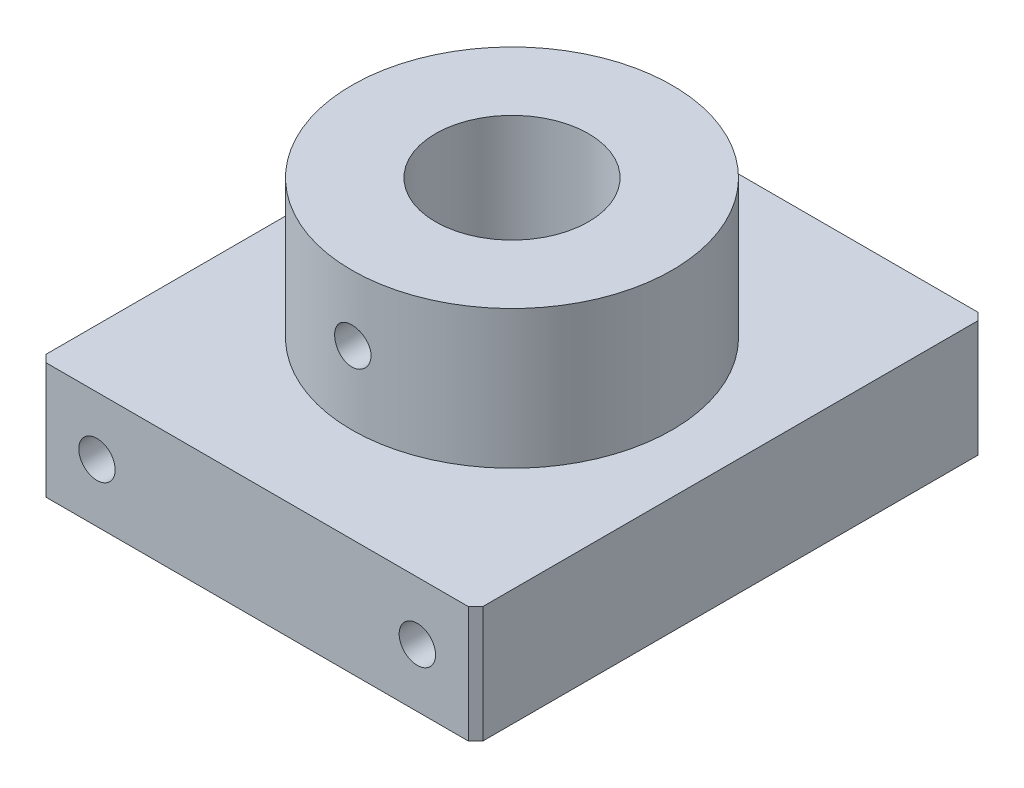
SolidWorks part; units mm, degrees
material "6061 合金"
ref_plane "前视基准面" through (0, 0, 0) normal (0, 0, 1) x (1, 0, 0)
ref_plane "上视基准面" through (0, 0, 0) normal (0, 1, 0) x (1, 0, 0)
ref_plane "右视基准面" through (0, 0, 0) normal (1, 0, 0) x (0, 0, -1)
sketch "草图1" plane through (0, 0, 0) normal (0, 1, 0) x (1, 0, 0)
  line L1 (-15, 17.5) -> (15, 17.5)
  line L2 (-15, 17.5) -> (-15, -17.5)
  line L3 (-15, -17.5) -> (15, -17.5)
  line L4 (15, 17.5) -> (15, -17.5)
  line L5 (-15, 17.5) -> (15, -17.5) construction
  line L6 (-15, -17.5) -> (15, 17.5) construction
  point P0 (0, 0)
  dimension "D1" = 35
  dimension "D2" = 30
extrude "凸台-拉伸1" add sketch "草图1" along normal blind 10
sketch "草图2" plane through (0, 0, 17.5) normal (0, 0, 1) x (1, 0, 0)
  line L0 (0, 0) -> (0, 10) construction
  line L4 (-15, 10) -> (15, 10) construction
  circle A0 centre (-11, 5) radius 1.25
  circle A1 centre (11, 5) radius 1.25
  dimension "D1" = 2.5
sketch "草图3" plane through (0, 10, 0) normal (0, 1, 0) x (1, 0, 0)
  circle A0 centre (0, 0) radius 11
  circle A1 centre (0, 0) radius 5.25
  dimension "D1" = 22
  dimension "D2" = 10.5
extrude "凸台-拉伸2" add sketch "草图3" along normal blind 8.5
sketch "草图4" plane through (0, 0, 0) normal (0, 0, 1) x (1, 0, 0)
  line L1 (5.25, 18.5) -> (-5.25, 18.5) construction
  circle A0 centre (0, 14) radius 1.25
  dimension "D1" = 2.5
  dimension "D2" = 4.5
chamfer "倒角1" distance 0.5 angle 45 4 edges at (15, 5, -17.5) (-15, 5, -17.5) (-15, 5, 17.5) (15, 5, 17.5)
sketch "草图6" plane through (0, 18.5, 0) normal (0, 1, 0) x (1, 0, 0)
  circle A0 centre (0, 0) radius 5.25
extrude "切除-拉伸3" cut sketch "草图6" against normal through all
sketch "草图7" plane through (0, 0, 0) normal (0, -1, 0) x (1, 0, 0)
  line L1 (-15.5971, 18.4355) -> (15.5971, 18.4355)
  line L2 (-15.5971, 18.4355) -> (-15.5971, -18.4355)
  line L3 (-15.5971, -18.4355) -> (15.5971, -18.4355)
  line L4 (15.5971, 18.4355) -> (15.5971, -18.4355)
  line L5 (-15.5971, 18.4355) -> (15.5971, -18.4355) construction
  line L6 (-15.5971, -18.4355) -> (15.5971, 18.4355) construction
  point P0 (0, 0)
extrude "切除-拉伸4" cut sketch "草图7" against normal blind 1
sketch "草图8" plane through (0, 10, 0) normal (0, 1, 0) x (1, 0, 0)
  line L1 (-16.7439, 18.8942) -> (16.7439, 18.8942)
  line L2 (-16.7439, 18.8942) -> (-16.7439, -18.8942)
  line L3 (-16.7439, -18.8942) -> (16.7439, -18.8942)
  line L4 (16.7439, 18.8942) -> (16.7439, -18.8942)
  line L5 (-16.7439, 18.8942) -> (16.7439, -18.8942) construction
  line L6 (-16.7439, -18.8942) -> (16.7439, 18.8942) construction
  circle A0 centre (0, 0) radius 11
extrude "切除-拉伸5" cut sketch "草图8" against normal blind 1
hole_wizard "M3 螺纹孔1" positions "3D草图1" profile "草图9" tap size "M3" standard "GB"
sketch3d "3D草图1"
  point P0 (-11, 5, 17.5)
  point P3 (11, 5, 17.5)
sketch "草图9" plane through (-11, 5, 17.5) normal (1, 0, 0) x (0, -1, 0)
  line L0 (0, 0) -> (0, 8.7511)
  line L1 (0, 8.7511) -> (1.25, 8)
  line L2 (1.25, 8) -> (1.25, 0)
  line L5 (1.25, 0) -> (0, 0)
  line L10 (0, 8.7511) -> (-1.25, 8) construction
  line L11 (0, -6.35) -> (0, 107.95) construction
  dimension "螺纹孔钻头直径" = 2.5
  dimension "螺纹孔钻头深度" = 8
  dimension "导头角度" = 118
cosmetic thread "孔螺蚊线1" parameters "D1"=6, "D2"=3
cosmetic thread "孔螺蚊线2" parameters "D1"=6, "D2"=3
mirror "镜向1" about plane through (0, 0, 0) normal (0, 0, 1) of "M3 螺纹孔1"
extrude "切除-拉伸6" cut sketch "草图4" along normal through all
cosmetic thread "装饰螺纹线1" parameters "D2"=3
